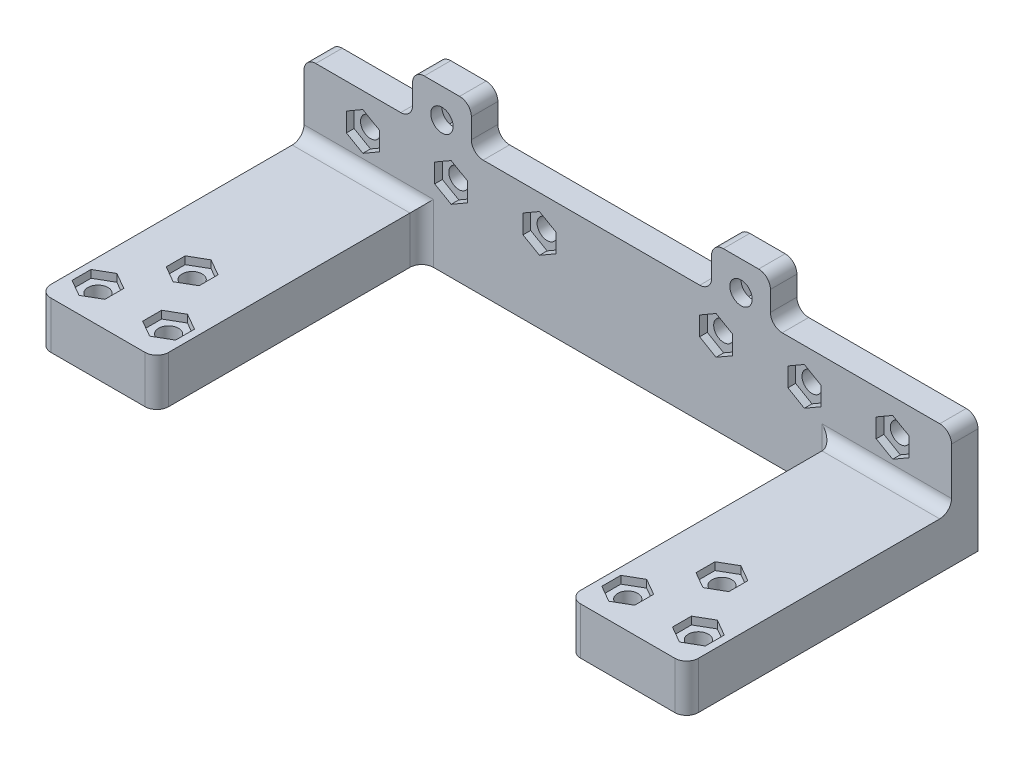
SolidWorks part; units mm, degrees
ref_plane "前视基准面" through (0, 0, 0) normal (0, 0, 1) x (1, 0, 0)
ref_plane "上视基准面" through (0, 0, 0) normal (0, 1, 0) x (1, 0, 0)
ref_plane "右视基准面" through (0, 0, 0) normal (1, 0, 0) x (0, 0, -1)
sketch "草图1" plane through (0, 0, 0) normal (0, 0, 1) x (1, 0, 0)
  line L6 (-55, 0) -> (55, 0)
  line L11 (55, 0) -> (55, 20)
  line L12 (55, 20) -> (-55, 20)
  line L13 (-55, 20) -> (-55, 0)
  line L14 (-45, 14) -> (45, 14) construction
  line L15 (0, 14) -> (0, 0) construction
  circle A6 centre (-45, 14) radius 1.7
  circle A7 centre (-30, 14) radius 1.7
  circle A8 centre (-15, 14) radius 1.7
  circle A9 centre (15, 14) radius 1.7
  circle A10 centre (30, 14) radius 1.7
  circle A11 centre (45, 14) radius 1.7
  dimension "D1" = 110
  dimension "D2" = 3.4
  dimension "D3" = 90
  dimension "D4" = 60
  dimension "D5" = 30
  dimension "D6" = 20
  dimension "D7" = 6
extrude "凸台-拉伸1" add sketch "草图1" along normal blind 4.5
sketch "草图2" plane through (0, 0, 4.5) normal (0, 0, 1) x (1, 0, 0)
  line L0 (0, 0) -> (0, 12.4325) construction
  line L1 (-55, 0) -> (-35, 0)
  line L2 (-55, 0) -> (-55, 8)
  line L3 (-55, 8) -> (-35, 8)
  line L4 (-35, 0) -> (-35, 8)
  line L5 (55, 0) -> (35, 0)
  line L6 (55, 0) -> (55, 8)
  line L7 (55, 8) -> (35, 8)
  line L8 (35, 0) -> (35, 8)
  dimension "D1" = 8
  dimension "D2" = 20
extrude "凸台-拉伸2" add sketch "草图2" along normal blind 45
sketch "草图3" plane through (0, 0, 4.5) normal (0, 0, 1) x (1, 0, 0)
  line L1 (-45, 17.22) -> (-47.7886, 15.61)
  line L2 (-47.7886, 15.61) -> (-47.7886, 12.39)
  line L3 (-47.7886, 12.39) -> (-45, 10.78)
  line L4 (-45, 10.78) -> (-42.2114, 12.39)
  line L5 (-42.2114, 12.39) -> (-42.2114, 15.61)
  line L6 (-42.2114, 15.61) -> (-45, 17.22)
  line L7 (-30, 17.22) -> (-32.7886, 15.61)
  line L8 (-32.7886, 15.61) -> (-32.7886, 12.39)
  line L9 (-32.7886, 12.39) -> (-30, 10.78)
  line L10 (-30, 10.78) -> (-27.2114, 12.39)
  line L11 (-27.2114, 12.39) -> (-27.2114, 15.61)
  line L12 (-27.2114, 15.61) -> (-30, 17.22)
  line L13 (-15, 17.22) -> (-17.7886, 15.61)
  line L14 (-17.7886, 15.61) -> (-17.7886, 12.39)
  line L15 (-17.7886, 12.39) -> (-15, 10.78)
  line L16 (-15, 10.78) -> (-12.2114, 12.39)
  line L17 (-12.2114, 12.39) -> (-12.2114, 15.61)
  line L18 (-12.2114, 15.61) -> (-15, 17.22)
  line L19 (15, 17.22) -> (12.2114, 15.61)
  line L20 (12.2114, 15.61) -> (12.2114, 12.39)
  line L21 (12.2114, 12.39) -> (15, 10.78)
  line L22 (15, 10.78) -> (17.7886, 12.39)
  line L23 (17.7886, 12.39) -> (17.7886, 15.61)
  line L24 (17.7886, 15.61) -> (15, 17.22)
  line L25 (30, 17.22) -> (27.2114, 15.61)
  line L26 (27.2114, 15.61) -> (27.2114, 12.39)
  line L27 (27.2114, 12.39) -> (30, 10.78)
  line L28 (30, 10.78) -> (32.7886, 12.39)
  line L29 (32.7886, 12.39) -> (32.7886, 15.61)
  line L30 (32.7886, 15.61) -> (30, 17.22)
  line L31 (45, 17.22) -> (42.2114, 15.61)
  line L32 (42.2114, 15.61) -> (42.2114, 12.39)
  line L33 (42.2114, 12.39) -> (45, 10.78)
  line L34 (45, 10.78) -> (47.7886, 12.39)
  line L35 (47.7886, 12.39) -> (47.7886, 15.61)
  line L36 (47.7886, 15.61) -> (45, 17.22)
  circle A0 centre (-45, 14) radius 2.7886 construction
  circle A1 centre (-30, 14) radius 2.7886 construction
  circle A2 centre (-15, 14) radius 2.7886 construction
  circle A3 centre (15, 14) radius 2.7886 construction
  circle A4 centre (30, 14) radius 2.7886 construction
  circle A5 centre (45, 14) radius 2.7886 construction
  dimension "D1" = 3.22
extrude "切除-拉伸1" cut sketch "草图3" against normal blind 1.3
sketch "草图4" plane through (0, 0, 4.5) normal (0, 0, 1) x (1, 0, 0)
  line L1 (24.2383, 27.3806) -> (14.2383, 27.3806)
  line L2 (24.2383, 27.3806) -> (24.2383, 17.3806)
  line L3 (24.2383, 17.3806) -> (14.2383, 17.3806)
  line L4 (14.2383, 27.3806) -> (14.2383, 17.3806)
  line L5 (24.2383, 27.3806) -> (14.2383, 17.3806) construction
  line L6 (24.2383, 17.3806) -> (14.2383, 27.3806) construction
  line L7 (-26.5617, 27.3806) -> (-36.5617, 27.3806)
  line L8 (-26.5617, 27.3806) -> (-26.5617, 17.3806)
  line L9 (-26.5617, 17.3806) -> (-36.5617, 17.3806)
  line L10 (-36.5617, 27.3806) -> (-36.5617, 17.3806)
  line L11 (-26.5617, 27.3806) -> (-36.5617, 17.3806) construction
  line L12 (-26.5617, 17.3806) -> (-36.5617, 27.3806) construction
  point P0 (19.2383, 22.3806)
  point P6 (-31.5617, 22.3806)
  dimension "D1" = 10
extrude "凸台-拉伸3" add sketch "草图4" against normal up to surface (4.5 mm away) up to face at (0, 10, 0)
sketch "草图5" plane through (0, 0, 4.5) normal (0, 0, 1) x (1, 0, 0)
  circle A0 centre (19.2383, 22.3806) radius 1.9
  circle A1 centre (-31.5617, 22.3806) radius 1.9
  dimension "D2" = 3.8
extrude "切除-拉伸2" cut sketch "草图5" against normal through all
sketch "草图6" plane through (0, 0, 0) normal (0, 0, -1) x (-1, 0, 0)
  line L1 (34.8617, 22.3806) -> (33.2117, 25.2385)
  line L2 (33.2117, 25.2385) -> (29.9117, 25.2385)
  line L3 (29.9117, 25.2385) -> (28.2617, 22.3806)
  line L4 (28.2617, 22.3806) -> (29.9117, 19.5227)
  line L5 (29.9117, 19.5227) -> (33.2117, 19.5227)
  line L6 (33.2117, 19.5227) -> (34.8617, 22.3806)
  line L7 (-15.9383, 22.3806) -> (-17.5883, 25.2385)
  line L8 (-17.5883, 25.2385) -> (-20.8883, 25.2385)
  line L9 (-20.8883, 25.2385) -> (-22.5383, 22.3806)
  line L10 (-22.5383, 22.3806) -> (-20.8883, 19.5227)
  line L11 (-20.8883, 19.5227) -> (-17.5883, 19.5227)
  line L12 (-17.5883, 19.5227) -> (-15.9383, 22.3806)
  circle A0 centre (31.5617, 22.3806) radius 2.8579 construction
  circle A1 centre (-19.2383, 22.3806) radius 2.8579 construction
  dimension "D1" = 3.3
extrude "切除-拉伸3" cut sketch "草图6" against normal blind 2.6
sketch "草图7" plane through (0, 0, 0) normal (0, -1, 0) x (1, 0, 0)
  circle A0 centre (-51, 43.5) radius 1.7
  circle A1 centre (-39, 43.5) radius 1.7
  circle A2 centre (-45, 33.5) radius 1.7
  circle A3 centre (39, 43.5) radius 1.7
  circle A4 centre (51, 43.5) radius 1.7
  circle A5 centre (45, 33.5) radius 1.7
  dimension "D1" = 3.4
extrude "切除-拉伸4" cut sketch "草图7" against normal through all contours A0 | A1 | A2 | A5 | A3 | A4
sketch "草图8" plane through (0, 8, 0) normal (0, 1, 0) x (1, 0, 0)
  line L1 (51, -46.72) -> (53.7886, -45.11)
  line L2 (53.7886, -45.11) -> (53.7886, -41.89)
  line L3 (53.7886, -41.89) -> (51, -40.28)
  line L4 (51, -40.28) -> (48.2114, -41.89)
  line L5 (48.2114, -41.89) -> (48.2114, -45.11)
  line L6 (48.2114, -45.11) -> (51, -46.72)
  line L7 (39, -46.72) -> (41.7886, -45.11)
  line L8 (41.7886, -45.11) -> (41.7886, -41.89)
  line L9 (41.7886, -41.89) -> (39, -40.28)
  line L10 (39, -40.28) -> (36.2114, -41.89)
  line L11 (36.2114, -41.89) -> (36.2114, -45.11)
  line L12 (36.2114, -45.11) -> (39, -46.72)
  line L13 (45, -36.72) -> (47.7886, -35.11)
  line L14 (47.7886, -35.11) -> (47.7886, -31.89)
  line L15 (47.7886, -31.89) -> (45, -30.28)
  line L16 (45, -30.28) -> (42.2114, -31.89)
  line L17 (42.2114, -31.89) -> (42.2114, -35.11)
  line L18 (42.2114, -35.11) -> (45, -36.72)
  line L19 (-39, -46.72) -> (-36.2114, -45.11)
  line L20 (-36.2114, -45.11) -> (-36.2114, -41.89)
  line L21 (-36.2114, -41.89) -> (-39, -40.28)
  line L22 (-39, -40.28) -> (-41.7886, -41.89)
  line L23 (-41.7886, -41.89) -> (-41.7886, -45.11)
  line L24 (-41.7886, -45.11) -> (-39, -46.72)
  line L25 (-51, -46.72) -> (-48.2114, -45.11)
  line L26 (-48.2114, -45.11) -> (-48.2114, -41.89)
  line L27 (-48.2114, -41.89) -> (-51, -40.28)
  line L28 (-51, -40.28) -> (-53.7886, -41.89)
  line L29 (-53.7886, -41.89) -> (-53.7886, -45.11)
  line L30 (-53.7886, -45.11) -> (-51, -46.72)
  line L31 (-45, -36.72) -> (-42.2114, -35.11)
  line L32 (-42.2114, -35.11) -> (-42.2114, -31.89)
  line L33 (-42.2114, -31.89) -> (-45, -30.28)
  line L34 (-45, -30.28) -> (-47.7886, -31.89)
  line L35 (-47.7886, -31.89) -> (-47.7886, -35.11)
  line L36 (-47.7886, -35.11) -> (-45, -36.72)
  circle A0 centre (51, -43.5) radius 2.7886 construction
  circle A1 centre (39, -43.5) radius 2.7886 construction
  circle A2 centre (45, -33.5) radius 2.7886 construction
  circle A3 centre (-39, -43.5) radius 2.7886 construction
  circle A4 centre (-51, -43.5) radius 2.7886 construction
  circle A5 centre (-45, -33.5) radius 2.7886 construction
  dimension "D1" = 3.22
extrude "切除-拉伸5" cut sketch "草图8" against normal blind 1.3
fillet "圆角1" radius 2 18 edges at (35, 4, 4.5) (35, 4, 49.5) (45, 8, 4.5) (-35, 4, 4.5) (-35, 4, 49.5) (-45, 8, 4.5) (-55, 20, 2.25) (-36.5617, 20, 2.25) (-26.5617, 20, 2.25) (-26.5617, 27.3806, 2.25) (-36.5617, 27.3806, 2.25) (14.2383, 20, 2.25) (14.2383, 27.3806, 2.25) (24.2383, 27.3806, 2.25) (24.2383, 20, 2.25) (55, 20, 2.25) (-55, 4, 49.5) (55, 4, 49.5)
